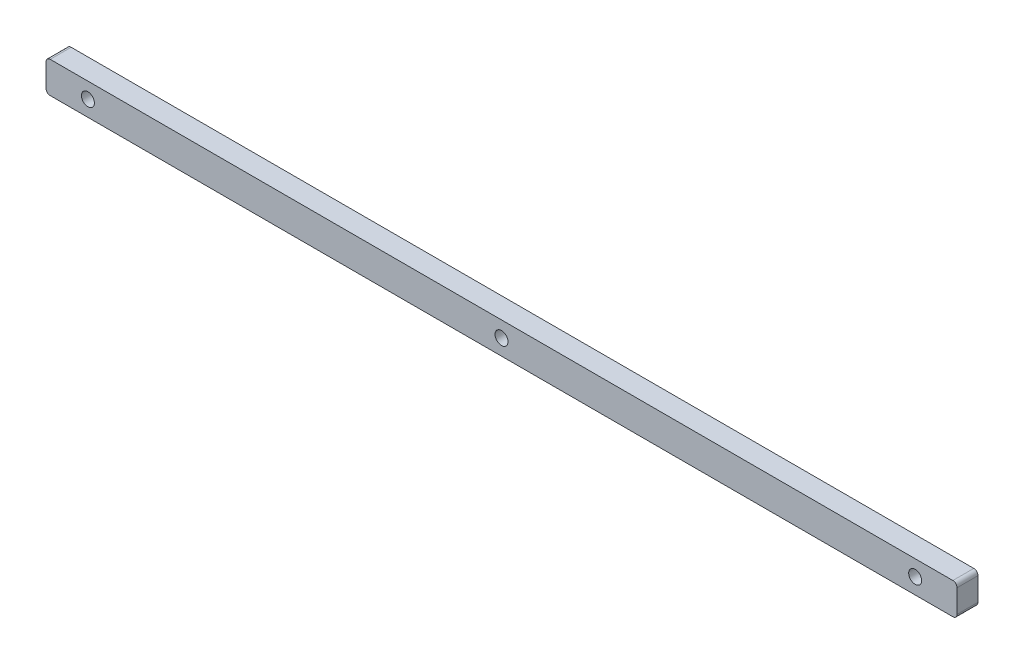
SolidWorks part; units mm, degrees
material "Balsa"
ref_plane "Front Plane" through (0, 0, 0) normal (0, 0, 1) x (1, 0, 0)
ref_plane "Top Plane" through (0, 0, 0) normal (0, 1, 0) x (1, 0, 0)
ref_plane "Right Plane" through (0, 0, 0) normal (1, 0, 0) x (0, 0, -1)
sketch "Sketch1" plane through (0, 0, 0) normal (0, 0, 1) x (1, 0, 0)
  line L1 (-276.225, -9.525) -> (276.225, -9.525)
  line L2 (-276.225, -9.525) -> (-276.225, 9.525)
  line L3 (-276.225, 9.525) -> (276.225, 9.525)
  line L4 (276.225, -9.525) -> (276.225, 9.525)
  circle A0 centre (0, 0) radius 3.937
  circle A1 centre (-250.825, 0) radius 3.937
  circle A2 centre (250.825, 0) radius 3.937
  point P0 (0, 0)
  point P12 (0, 0)
  point P13 (0, 0)
  dimension "D3" = 7.874
  dimension "D4" = 7.874
  dimension "D5" = 7.874
  dimension "D1" = 552.45
  dimension "D2" = 19.05
  dimension "D6" = 25.4
  dimension "D7" = 25.4
  dimension "D8" = 9.525
  dimension "D9" = 250.825
extrude "Boss-Extrude1" add sketch "Sketch1" along normal mid plane 12.7
fillet "Fillet1" radius 2.54 4 edges at (-276.225, 9.525, 0) (-276.225, -9.525, 0) (276.225, -9.525, 0) (276.225, 9.525, 0)
